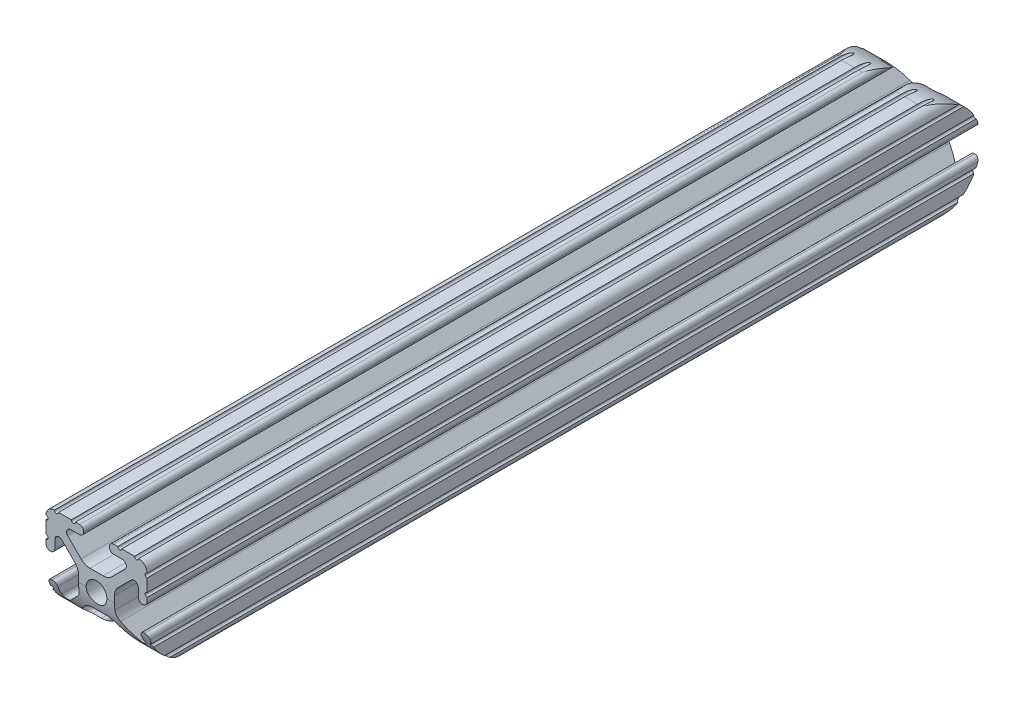
SolidWorks part; units mm, degrees
material "6061 Alloy"
ref_plane "Front Plane" through (0, 0, 0) normal (0, 0, 1) x (1, 0, 0)
ref_plane "Top Plane" through (0, 0, 0) normal (0, 1, 0) x (1, 0, 0)
ref_plane "Right Plane" through (0, 0, 0) normal (1, 0, 0) x (0, 0, -1)
sketch "Sketch1" plane through (0, 0, 0) normal (0, 0, 1) x (1, 0, 0)
  line L88 (-7.1797, -8.6452) -> (-3.9523, -5.4237)
  line L89 (-1.7093, -4.4958) -> (1.7093, -4.4958)
  line L90 (3.9523, -5.4237) -> (7.1797, -8.6452)
  line L91 (6.4164, -10.4902) -> (4.2875, -10.4902)
  line L92 (3.2385, -11.5392) -> (3.2385, -11.651)
  line L93 (4.2875, -12.7) -> (5.3171, -12.7)
  line L94 (6.3331, -12.7) -> (9.5504, -12.7)
  line L95 (12.7, -9.5504) -> (12.7, -6.3331)
  line L96 (12.7, -5.3171) -> (12.7, -4.2875)
  line L97 (11.651, -3.2385) -> (11.5392, -3.2385)
  line L98 (10.4902, -4.2875) -> (10.4902, -6.4021)
  line L99 (8.7371, -7.1294) -> (5.441, -3.8408)
  line L100 (4.5085, -1.5932) -> (4.5085, 1.5932)
  line L101 (5.441, 3.8408) -> (8.7371, 7.1294)
  line L102 (10.4902, 6.4021) -> (10.4902, 4.2875)
  line L103 (11.5392, 3.2385) -> (11.651, 3.2385)
  line L104 (12.7, 4.2875) -> (12.7, 5.3171)
  line L105 (12.7, 6.3331) -> (12.7, 9.5504)
  line L106 (9.5504, 12.7) -> (6.3331, 12.7)
  line L107 (5.3171, 12.7) -> (4.2875, 12.7)
  line L108 (3.2385, 11.651) -> (3.2385, 11.5392)
  line L109 (4.2875, 10.4902) -> (6.4768, 10.4902)
  line L110 (7.207, 8.7244) -> (3.8983, 5.4232)
  line L111 (1.6558, 4.4958) -> (-1.6558, 4.4958)
  line L112 (-3.8983, 5.4232) -> (-7.207, 8.7244)
  line L113 (-6.4768, 10.4902) -> (-4.2875, 10.4902)
  line L114 (-3.2385, 11.5392) -> (-3.2385, 11.651)
  line L115 (-4.2875, 12.7) -> (-5.3171, 12.7)
  line L116 (-6.3331, 12.7) -> (-9.5504, 12.7)
  line L117 (-12.7, 9.5504) -> (-12.7, 6.3331)
  line L118 (-12.7, 5.3171) -> (-12.7, 4.2875)
  line L119 (-11.651, 3.2385) -> (-11.5392, 3.2385)
  line L120 (-10.4902, 4.2875) -> (-10.4902, 6.4021)
  line L121 (-8.7371, 7.1294) -> (-5.441, 3.8408)
  line L122 (-4.5085, 1.5932) -> (-4.5085, -1.5932)
  line L123 (-5.441, -3.8408) -> (-8.7371, -7.1294)
  line L124 (-10.4902, -6.4021) -> (-10.4902, -4.2875)
  line L125 (-11.5392, -3.2385) -> (-11.651, -3.2385)
  line L126 (-12.7, -4.2875) -> (-12.7, -5.3171)
  line L127 (-12.7, -6.3331) -> (-12.7, -9.5504)
  line L128 (-9.5504, -12.7) -> (-6.3331, -12.7)
  line L129 (-5.3171, -12.7) -> (-4.2875, -12.7)
  line L130 (-3.2385, -11.651) -> (-3.2385, -11.5392)
  line L131 (-4.2875, -10.4902) -> (-6.4164, -10.4902)
  circle A1 centre (0, 0) radius 2.6035
  arc A104 (-7.1797, -8.6452) -> (-6.4164, -10.4902) centre (-6.4164, -9.4098) ccw
  arc A105 (-1.7093, -4.4958) -> (-3.9523, -5.4237) centre (-1.7093, -7.6708) ccw
  arc A106 (3.9523, -5.4237) -> (1.7093, -4.4958) centre (1.7093, -7.6708) ccw
  arc A107 (6.4164, -10.4902) -> (7.1797, -8.6452) centre (6.4164, -9.4098) ccw
  arc A108 (4.2875, -10.4902) -> (3.2385, -11.5392) centre (4.2875, -11.5392) ccw
  arc A109 (3.2385, -11.651) -> (4.2875, -12.7) centre (4.2875, -11.651) ccw
  arc A110 (6.3331, -12.7) -> (5.3171, -12.7) centre (5.8251, -12.7) ccw
  arc A111 (10.5664, -12.6998) -> (9.5504, -12.7) centre (10.0584, -12.7) ccw
  arc A112 (10.5664, -12.6998) -> (12.6998, -10.5664) centre (10.5918, -10.5918) ccw
  arc A113 (12.7, -9.5504) -> (12.6998, -10.5664) centre (12.7, -10.0584) ccw
  arc A114 (12.7, -5.3171) -> (12.7, -6.3331) centre (12.7, -5.8251) ccw
  arc A115 (12.7, -4.2875) -> (11.651, -3.2385) centre (11.651, -4.2875) ccw
  arc A116 (11.5392, -3.2385) -> (10.4902, -4.2875) centre (11.5392, -4.2875) ccw
  arc A117 (8.7371, -7.1294) -> (10.4902, -6.4021) centre (9.4628, -6.4021) ccw
  arc A118 (4.5085, -1.5932) -> (5.441, -3.8408) centre (7.6835, -1.5932) ccw
  arc A119 (5.441, 3.8408) -> (4.5085, 1.5932) centre (7.6835, 1.5932) ccw
  arc A120 (10.4902, 6.4021) -> (8.7371, 7.1294) centre (9.4628, 6.4021) ccw
  arc A121 (10.4902, 4.2875) -> (11.5392, 3.2385) centre (11.5392, 4.2875) ccw
  arc A122 (11.651, 3.2385) -> (12.7, 4.2875) centre (11.651, 4.2875) ccw
  arc A123 (12.7, 6.3331) -> (12.7, 5.3171) centre (12.7, 5.8251) ccw
  arc A124 (12.6998, 10.5664) -> (12.7, 9.5504) centre (12.7, 10.0584) ccw
  arc A125 (12.6998, 10.5664) -> (10.5664, 12.6998) centre (10.5918, 10.5918) ccw
  arc A126 (9.5504, 12.7) -> (10.5664, 12.6998) centre (10.0584, 12.7) ccw
  arc A127 (5.3171, 12.7) -> (6.3331, 12.7) centre (5.8251, 12.7) ccw
  arc A128 (4.2875, 12.7) -> (3.2385, 11.651) centre (4.2875, 11.651) ccw
  arc A129 (3.2385, 11.5392) -> (4.2875, 10.4902) centre (4.2875, 11.5392) ccw
  arc A130 (7.207, 8.7244) -> (6.4768, 10.4902) centre (6.4768, 9.4563) ccw
  arc A131 (1.6558, 4.4958) -> (3.8983, 5.4232) centre (1.6558, 7.6708) ccw
  arc A132 (-3.8983, 5.4232) -> (-1.6558, 4.4958) centre (-1.6558, 7.6708) ccw
  arc A133 (-6.4768, 10.4902) -> (-7.207, 8.7244) centre (-6.4768, 9.4563) ccw
  arc A134 (-4.2875, 10.4902) -> (-3.2385, 11.5392) centre (-4.2875, 11.5392) ccw
  arc A135 (-3.2385, 11.651) -> (-4.2875, 12.7) centre (-4.2875, 11.651) ccw
  arc A136 (-6.3331, 12.7) -> (-5.3171, 12.7) centre (-5.8251, 12.7) ccw
  arc A137 (-10.5664, 12.6998) -> (-9.5504, 12.7) centre (-10.0584, 12.7) ccw
  arc A138 (-10.5664, 12.6998) -> (-12.6998, 10.5664) centre (-10.5918, 10.5918) ccw
  arc A139 (-12.7, 9.5504) -> (-12.6998, 10.5664) centre (-12.7, 10.0584) ccw
  arc A140 (-12.7, 5.3171) -> (-12.7, 6.3331) centre (-12.7, 5.8251) ccw
  arc A141 (-12.7, 4.2875) -> (-11.651, 3.2385) centre (-11.651, 4.2875) ccw
  arc A142 (-11.5392, 3.2385) -> (-10.4902, 4.2875) centre (-11.5392, 4.2875) ccw
  arc A143 (-8.7371, 7.1294) -> (-10.4902, 6.4021) centre (-9.4628, 6.4021) ccw
  arc A144 (-4.5085, 1.5932) -> (-5.441, 3.8408) centre (-7.6835, 1.5932) ccw
  arc A145 (-5.441, -3.8408) -> (-4.5085, -1.5932) centre (-7.6835, -1.5932) ccw
  arc A146 (-10.4902, -6.4021) -> (-8.7371, -7.1294) centre (-9.4628, -6.4021) ccw
  arc A147 (-10.4902, -4.2875) -> (-11.5392, -3.2385) centre (-11.5392, -4.2875) ccw
  arc A148 (-11.651, -3.2385) -> (-12.7, -4.2875) centre (-11.651, -4.2875) ccw
  arc A149 (-12.7, -6.3331) -> (-12.7, -5.3171) centre (-12.7, -5.8251) ccw
  arc A150 (-12.6998, -10.5664) -> (-12.7, -9.5504) centre (-12.7, -10.0584) ccw
  arc A151 (-12.6998, -10.5664) -> (-10.5664, -12.6998) centre (-10.5918, -10.5918) ccw
  arc A152 (-9.5504, -12.7) -> (-10.5664, -12.6998) centre (-10.0584, -12.7) ccw
  arc A153 (-5.3171, -12.7) -> (-6.3331, -12.7) centre (-5.8251, -12.7) ccw
  arc A154 (-4.2875, -12.7) -> (-3.2385, -11.651) centre (-4.2875, -11.651) ccw
  arc A155 (-3.2385, -11.5392) -> (-4.2875, -10.4902) centre (-4.2875, -11.5392) ccw
extrude "Boss-Extrude1" add sketch "Sketch1" along normal mid plane 209.55
sketch "Sketch2" plane through (4.5085, 0, 0) normal (1, 0, 0) x (0, 0, -1)
  line L0 (-104.775, -1.5932) -> (-104.775, 1.5932) construction
  line L1 (-104.775, -12.6998) -> (104.775, -12.6998) construction
  line L2 (-104.775, 0) -> (-104.775, -12.7)
  line L3 (-104.775, -12.7) -> (-92.075, -12.7)
  line L4 (-104.775, -12.7) -> (104.775, -12.7) construction
  circle A0 centre (-92.075, 0) radius 3.175
  circle A1 centre (-66.675, 0) radius 3.175
  arc A2 (-104.775, 0) -> (-92.075, -12.7) centre (-92.075, 0) ccw
  dimension "D1" = 6.35
  dimension "D2" = 12.7
  dimension "D3" = 12.6998
  dimension "D4" = 25.4
extrude "Cut-Extrude1" cut sketch "Sketch2" against normal through all both and the other way through all
sketch "Sketch3" plane through (4.5085, 0, 0) normal (1, 0, 0) x (0, 0, -1)
  line L0 (104.775, 6.3331) -> (104.775, 9.5504) construction
  line L1 (104.775, -1.5932) -> (104.775, 1.5932) construction
  line L2 (-104.775, 12.7) -> (104.775, 12.7) construction
  line L3 (92.075, 12.7) -> (104.775, 12.7)
  line L4 (104.775, 12.7) -> (104.775, -12.7)
  line L5 (104.775, -12.7) -> (92.075, -12.7)
  circle A0 centre (92.075, 0) radius 12.7 construction
  arc A1 (92.075, 12.7) -> (92.075, -12.7) centre (92.075, 0) cw
  line M2 (104.775, 1.5932) -> (-63.9287, 1.5932)
  line M4 (-63.9287, -1.5932) -> (104.775, -1.5932)
  dimension "D1" = 12.7
extrude "Cut-Extrude2" cut sketch "Sketch3" against normal through all both and the other way through all contours L3 A1 L4 M2 | A1 L5 L4 M4
